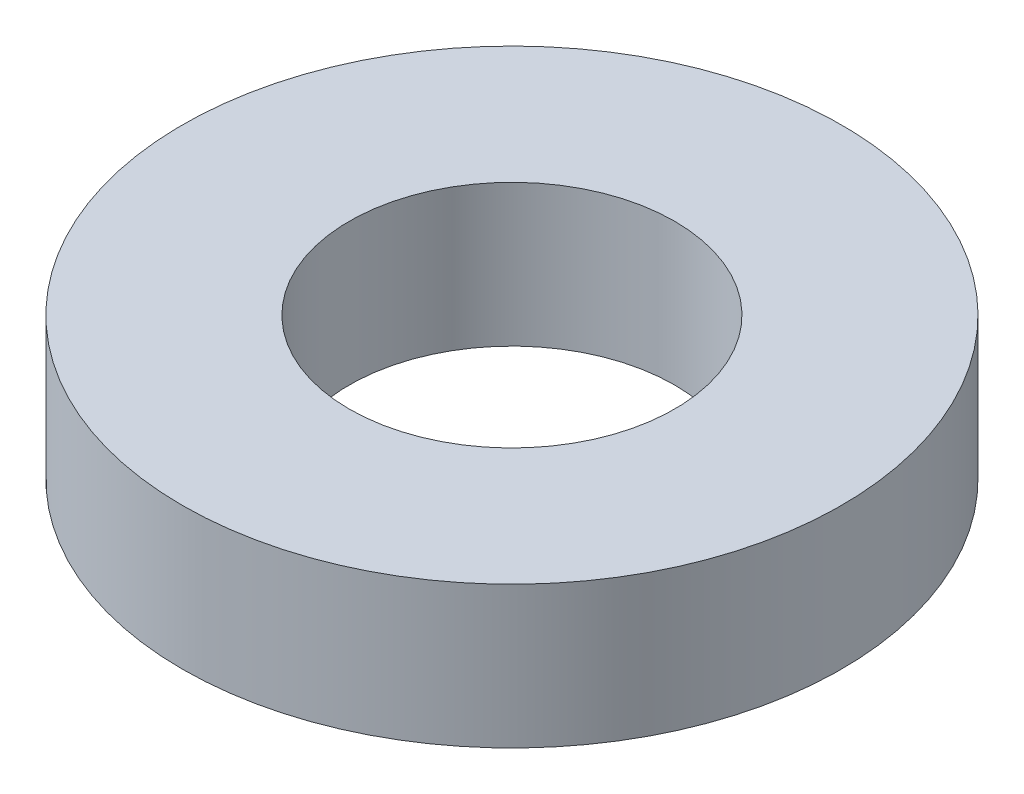
SolidWorks part; units mm, degrees
ref_plane "前视基准面" through (0, 0, 0) normal (0, 0, 1) x (1, 0, 0)
ref_plane "上视基准面" through (0, 0, 0) normal (0, 1, 0) x (1, 0, 0)
ref_plane "右视基准面" through (0, 0, 0) normal (1, 0, 0) x (0, 0, -1)
sketch "草图1" plane through (0, 0, 0) normal (0, 1, 0) x (1, 0, 0)
  circle A0 centre (0, 0) radius 19.5
  circle A1 centre (0, 0) radius 39.5
extrude "凸台-拉伸1" add sketch "草图1" along normal blind 17
